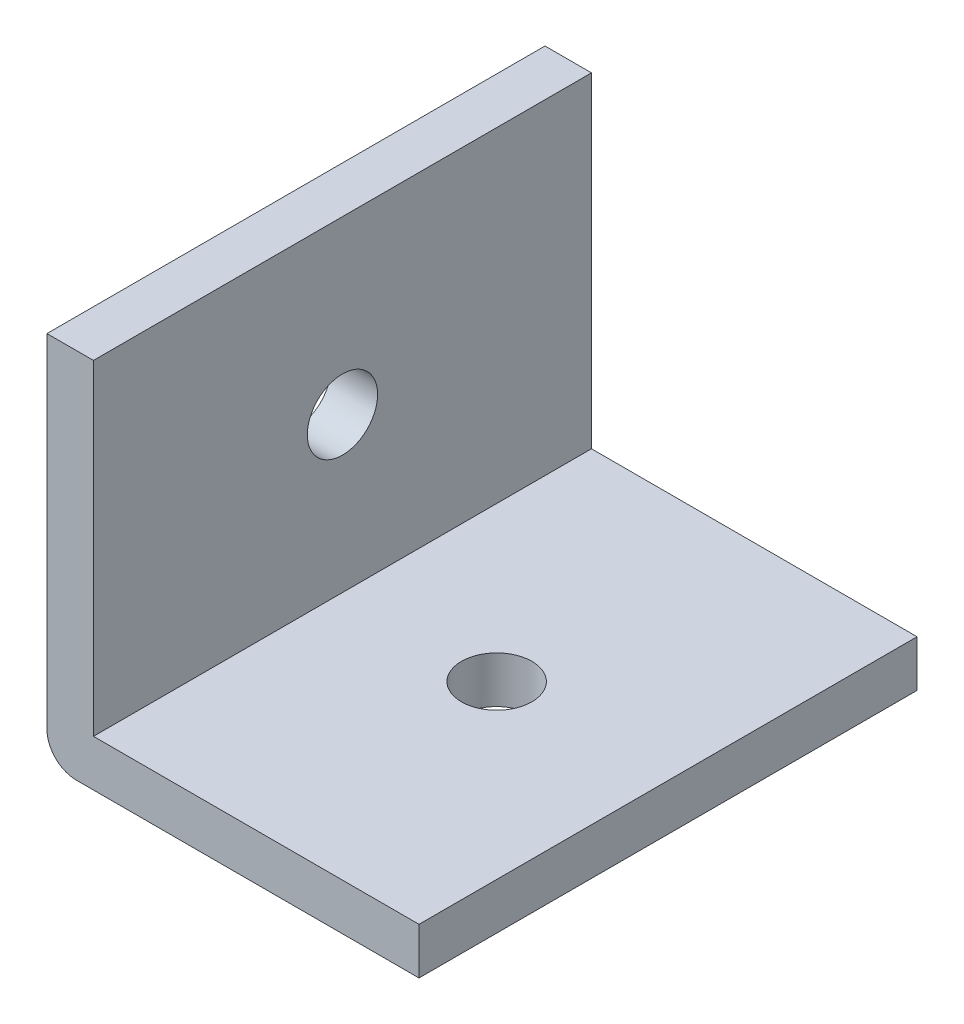
SolidWorks part; units mm, degrees
material "6061 Alloy"
ref_plane "Front Plane" through (0, 0, 0) normal (0, 0, 1) x (1, 0, 0)
ref_plane "Top Plane" through (0, 0, 0) normal (0, 1, 0) x (1, 0, 0)
ref_plane "Right Plane" through (0, 0, 0) normal (1, 0, 0) x (0, 0, -1)
sketch "Sketch1" plane through (0, 0, 0) normal (0, 1, 0) x (1, 0, 0)
  line L1 (0, 0) -> (12.7, 0)
  line L2 (0, 0) -> (0, -17)
  line L3 (0, -17) -> (12.7, -17)
  line L4 (12.7, 0) -> (12.7, -17)
  dimension "D1" = 12.7
  dimension "D2" = 17
extrude "Boss-Extrude1" add sketch "Sketch1" along normal blind 1.5875
sketch "Sketch2" plane through (0, 1.5875, 0) normal (0, 1, 0) x (1, 0, 0)
  line L0 (0, -17) -> (12.7, -17) construction
  line L1 (0, 0) -> (1.5875, 0)
  line L2 (0, 0) -> (0, -17)
  line L3 (0, -17) -> (1.5875, -17)
  line L4 (1.5875, 0) -> (1.5875, -17)
  dimension "D1" = 1.5875
extrude "Boss-Extrude2" add sketch "Sketch2" along normal blind 11.1125
fillet "Fillet1" radius 1 1 edges at (0, 0, 8.5)
hole_wizard "M2 Clearance Hole1" positions "Sketch3" profile "Sketch5" hole size "M2" standard "ANSI Metric"
sketch "Sketch3" plane through (0, 0, 0) normal (0, -1, 0) x (-1, 0, 0)
  line L0 (-12.7, 0) -> (-1, 0) construction
  line L1 (-12.7, -17) -> (-12.7, 0) construction
  point P0 (-6.85, -8.5)
  dimension "D1" = 8.5
  dimension "D2" = 5.85
sketch "Sketch5" plane through (6.85, 0, 8.5) normal (1, 0, 0) x (0, 0, -1)
  line L0 (0, 0) -> (0, 2.721)
  line L1 (0, 2.721) -> (1.2, 2)
  line L2 (1.2, 2) -> (1.2, 0)
  line L5 (1.2, 0) -> (0, 0)
  line L10 (0, 2.721) -> (-1.2, 2) construction
  line L11 (0, -6.35) -> (0, 107.95) construction
  dimension "Hole Dia." = 2.4
  dimension "Hole Depth" = 2
  dimension "Drill Angle" = 118
hole_wizard "M2 Clearance Hole2" positions "Sketch6" profile "Sketch7" hole size "M2" standard "ANSI Metric"
sketch "Sketch6" plane through (0, 0, 0) normal (-1, 0, 0) x (0, 0, 1)
  line L1 (0, 12.7) -> (0, 1) construction
  line L2 (0, 1) -> (17, 1) construction
  point P0 (8.5, 6.85)
  point P11 (15.5882, 19.3491)
  dimension "D1" = 8.5
  dimension "D2" = 5.85
sketch "Sketch7" plane through (0, 6.85, 8.5) normal (0, 1, 0) x (0, 0, 1)
  line L0 (0, 0) -> (0, 2.721)
  line L1 (0, 2.721) -> (1.2, 2)
  line L2 (1.2, 2) -> (1.2, 0)
  line L5 (1.2, 0) -> (0, 0)
  line L10 (0, 2.721) -> (-1.2, 2) construction
  line L11 (0, -6.35) -> (0, 107.95) construction
  dimension "Hole Dia." = 2.4
  dimension "Hole Depth" = 2
  dimension "Drill Angle" = 118
